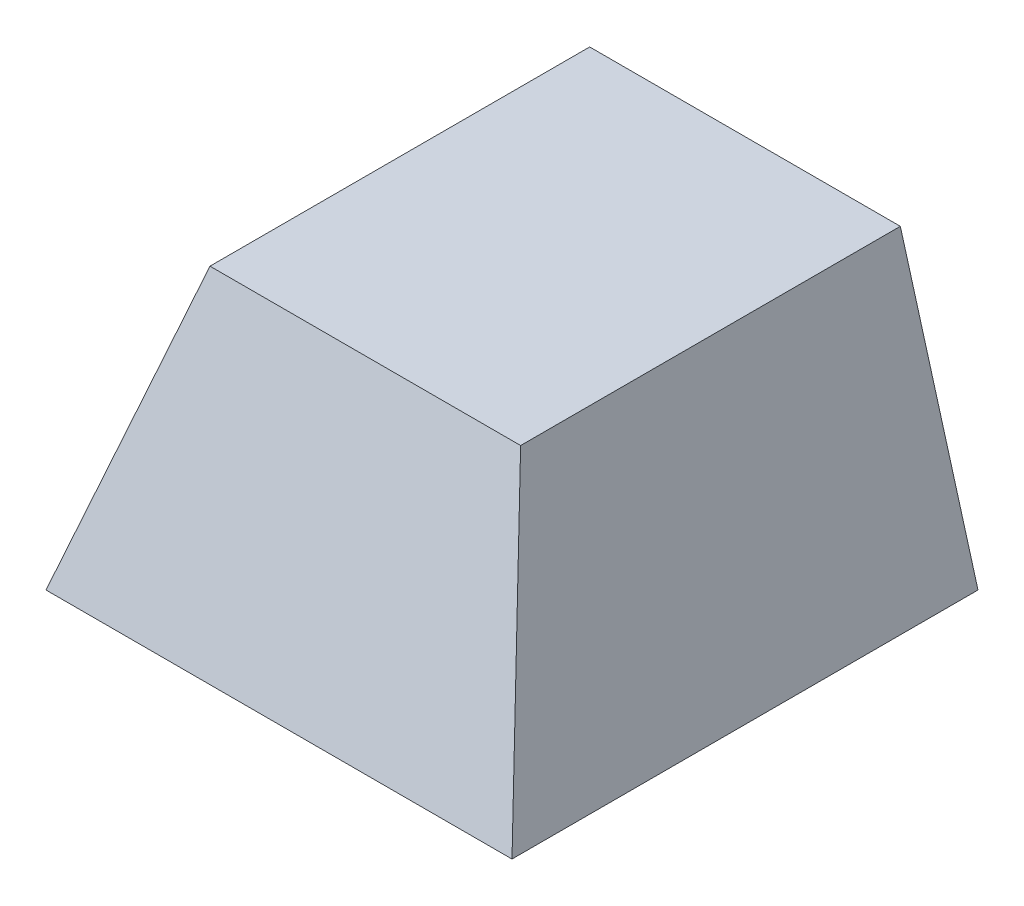
SolidWorks part; units mm, degrees
ref_plane "Front Plane" through (0, 0, 0) normal (0, 0, 1) x (1, 0, 0)
ref_plane "Top Plane" through (0, 0, 0) normal (0, 1, 0) x (1, 0, 0)
ref_plane "Right Plane" through (0, 0, 0) normal (1, 0, 0) x (0, 0, -1)
sketch "Sketch1" plane through (0, 0, 0) normal (0, 0, 1) x (1, 0, 0)
  line L0 (-124.4923, -61.6423) -> (-79.4923, 98.3577)
  line L5 (-124.4923, -61.6423) -> (145.5077, -61.6423)
  line L9 (10.5077, 98.3577) -> (10.5077, -61.6423) construction
  line L10 (-79.4923, 98.3577) -> (100.5077, 98.3577)
  line L11 (145.5077, -61.6423) -> (100.5077, 98.3577)
  dimension "D1" = 270
  dimension "D2" = 160
  dimension "D3" = 90
extrude "Boss-Extrude1" add sketch "Sketch1" along normal blind 270
sketch "Sketch3" plane through (-99.3006, 27.9283, 0) normal (-0.9627, 0.2707, 0) x (0, 0, 1)
  line L0 (135, 73.1619) -> (135, -93.0458) construction
  line L1 (270, 73.1619) -> (0, 73.1619) construction
  line L2 (270, -93.0458) -> (0, -93.0458) construction
  line L3 (0, 73.1619) -> (220, 73.1619)
  line L8 (220, 73.1619) -> (270, 73.1619)
  line L9 (270, 73.1619) -> (270, -93.0458)
  line L10 (220, 73.1619) -> (270, -93.0458)
  point P12 (182.682, 73.1619)
  line M6 (270, -93.0458) -> (270, 73.1619)
  line M7 (270, 73.1619) -> (0, 73.1619)
  dimension "D1" = 220
extrude "Cut-Extrude2" cut sketch "Sketch3" along direction (-1, 0, 0) on the side against the normal blind 280 contours L10 M7 M6
sketch "Sketch5" plane through (0, 0, 0) normal (0, 0, -1) x (-1, 0, 0)
  line L0 (-145.5077, -61.6423) -> (124.4923, -61.6423)
  line L1 (124.4923, -61.6423) -> (79.4923, 98.3577)
  line L2 (79.4923, 98.3577) -> (-100.5077, 98.3577)
  line L3 (-100.5077, 98.3577) -> (-145.5077, -61.6423)
  dimension "D1" = 180
  dimension "D2" = 166.2077
  dimension "D3" = 270
  dimension "D4" = 166.2077
sketch "Sketch6" plane through (0, 98.3577, 0) normal (0, 1, 0) x (1, 0, 0)
  line L1 (100.5077, -220) -> (-79.4923, -220)
  line L2 (100.5077, -220) -> (100.5077, 0)
  line L3 (100.5077, 0) -> (-79.4923, 0)
  line L4 (-79.4923, -220) -> (-79.4923, 0)
  dimension "D1" = 180
  dimension "D2" = 220
